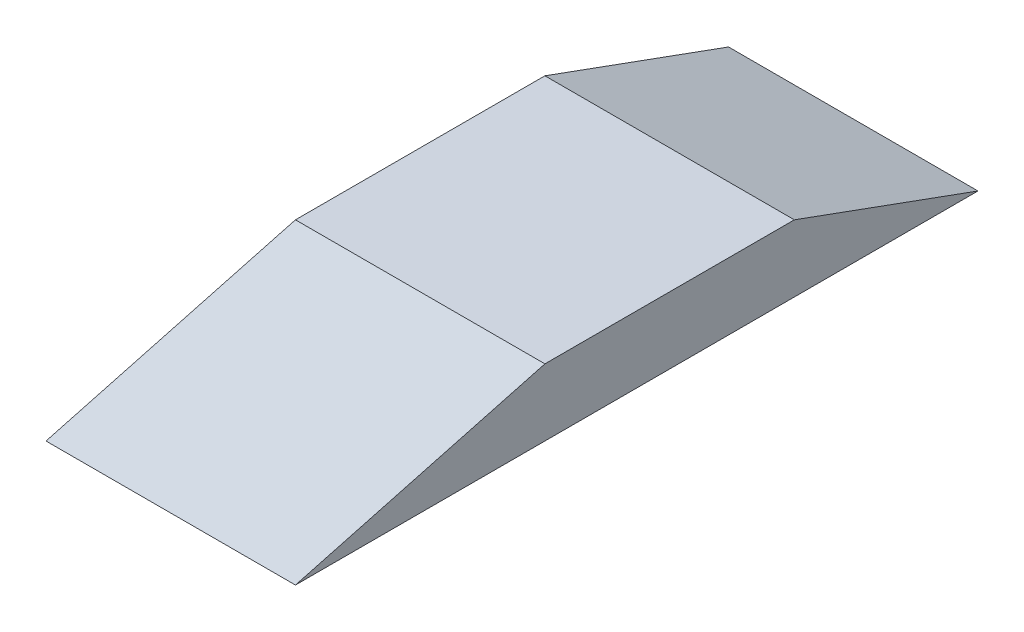
SolidWorks part; units mm, degrees
ref_plane "Front" through (0, 0, 0) normal (0, 0, 1) x (1, 0, 0)
ref_plane "Top" through (0, 0, 0) normal (0, 1, 0) x (1, 0, 0)
ref_plane "Right" through (0, 0, 0) normal (1, 0, 0) x (0, 0, -1)
sketch "草图1" plane through (0, 0, 0) normal (1, 0, 0) x (0, 0, -1)
  line L0 (0, 0) -> (1500, 0)
  line L1 (1500, 0) -> (1500, 401.9238)
  line L2 (1500, 401.9238) -> (0, 0)
  line L3 (0, 0) -> (0, 291.1762) construction
  line L4 (1500, 401.9238) -> (3000, 401.9238)
  line L5 (3000, 401.9238) -> (4104.2765, 0)
  line L6 (4104.2765, 0) -> (1500, 0)
  dimension "D1" = 15
  dimension "D2" = 1500
  dimension "D3" = 20
  dimension "D4" = 1500
extrude "凸台-拉伸1" add sketch "草图1" along normal blind 1500 contours L6 L5 L4 L1 | L1 L2 L0
